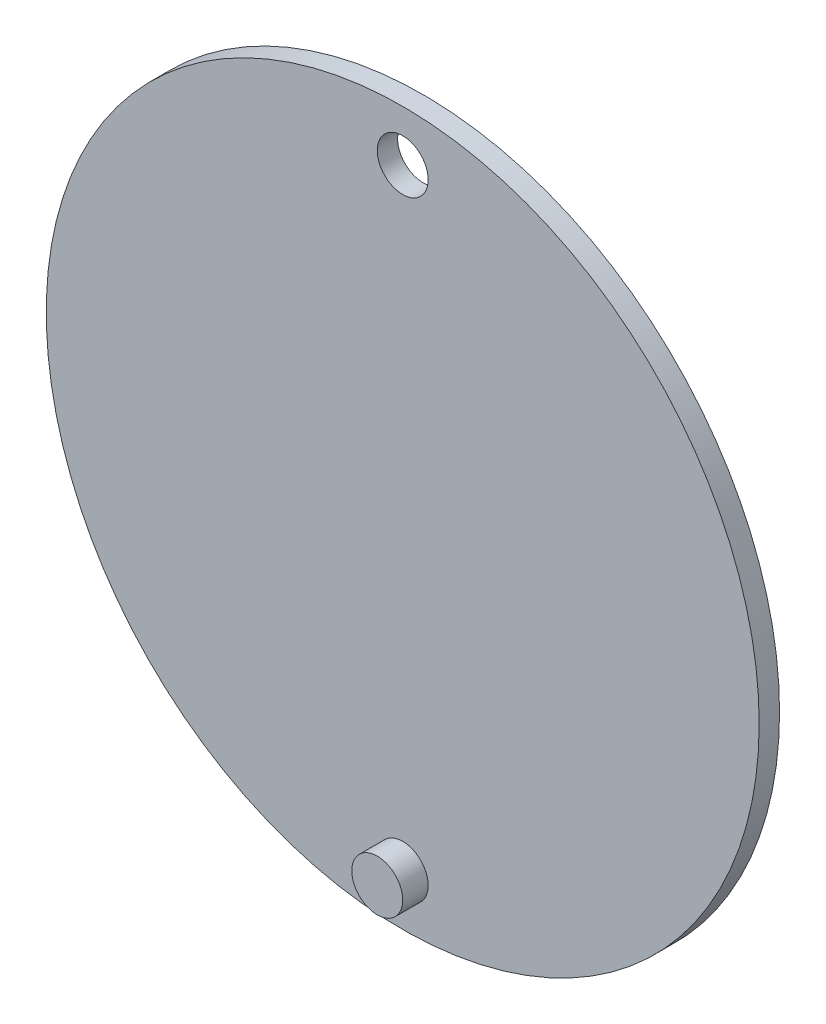
SolidWorks part; units mm, degrees
ref_plane "Front Plane" through (0, 0, 0) normal (0, 0, 1) x (1, 0, 0)
ref_plane "Top Plane" through (0, 0, 0) normal (0, 1, 0) x (1, 0, 0)
ref_plane "Right Plane" through (0, 0, 0) normal (1, 0, 0) x (0, 0, -1)
sketch "Sketch1" plane through (0, 0, 0) normal (0, 0, 1) x (1, 0, 0)
  line L0 (-169.7289, -88.9) -> (169.7289, -88.9) construction
  line L1 (-97.9706, 88.9) -> (97.9706, 88.9) construction
  circle A0 centre (0, 0) radius 88.9
  circle A1 centre (0, 0) radius 6
  circle A2 centre (0, -76.2) radius 6.35
  circle A3 centre (0, 76.2) radius 6.35
  point P7 (0, -88.9)
  point P14 (0, 88.9)
  dimension "D1" = 177.8
  dimension "D2" = 12.7
  dimension "D3" = 12
  dimension "D5" = 12.7
  dimension "D4" = 12.7
  dimension "D6" = 12.7
extrude "Boss-Extrude1" add sketch "Sketch1" along normal blind 5.08
sketch "Sketch2" plane through (0, 0, 0) normal (0, 0, 1) x (1, 0, 0)
  circle A0 centre (0, -76.2) radius 6.35
extrude "Boss-Extrude2" add sketch "Sketch2" along normal blind 11.43
ref_plane "Plane1" through (0, 0, 5.08) normal (0, 0, -1) x (-1, 0, 0)
sketch "Sketch3" plane through (0, 0, 5.08) normal (0, 0, 1) x (1, 0, 0)
  circle A0 centre (0, 0) radius 6.35
extrude "Boss-Extrude3" add sketch "Sketch3" against normal blind 50.8
ref_plane "Plane2" through (0, 0, -45.72) normal (0, 0, -1) x (-1, 0, 0)
sketch "Sketch4" plane through (0, 0, -45.72) normal (0, 0, -1) x (-1, 0, 0)
  line L0 (3.05, 2.6646) -> (3.05, -2.6646)
  arc A0 (3.05, 2.6646) -> (3.05, -2.6646) centre (0, 0) ccw
  dimension "D1" = 4.05
  dimension "D2" = 3.05
extrude "Cut-Extrude1" cut sketch "Sketch4" against normal blind 18
